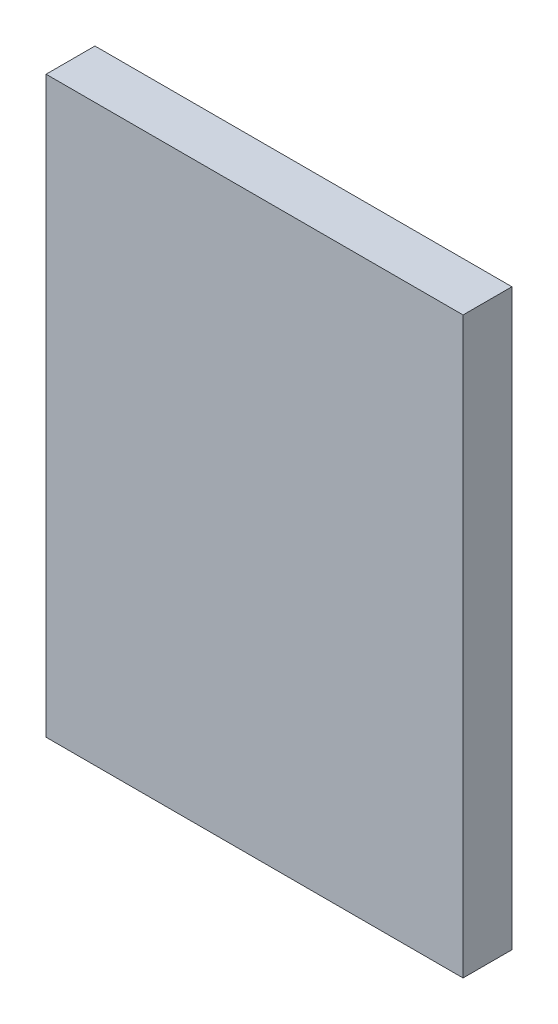
SolidWorks part; units mm, degrees
ref_plane "Front Plane" through (0, 0, 0) normal (0, 0, 1) x (1, 0, 0)
ref_plane "Top Plane" through (0, 0, 0) normal (0, 1, 0) x (1, 0, 0)
ref_plane "Right Plane" through (0, 0, 0) normal (1, 0, 0) x (0, 0, -1)
ref_plane "PZ_p2_10" through (0, 0, 2.1) normal (0, 0, 1) x (1, 0, 0)
sketch "LCD_Sk1" plane through (0, 0, 2.1) normal (0, 0, 1) x (1, 0, 0)
  line L0 (-17.5, -25.8) -> (17.5, -25.8)
  line L1 (17.5, -25.8) -> (17.5, 22.4)
  line L2 (17.5, 22.4) -> (-17.5, 22.4)
  line L3 (-17.5, 22.4) -> (-17.5, -25.8)
extrude "LCD" add sketch "LCD_Sk1" against normal blind 4.1
